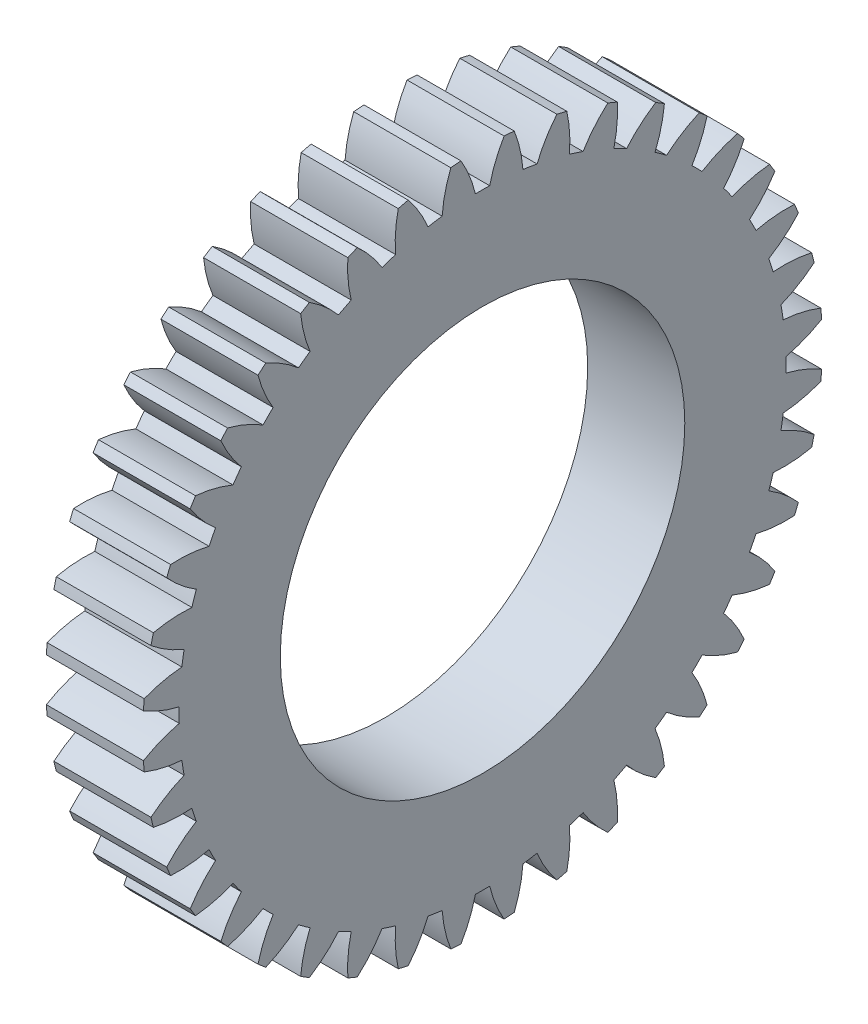
SolidWorks part; units mm, degrees
ref_plane "Plane1" through (0, 0, 0) normal (0, 0, 1) x (1, 0, 0)
ref_plane "Plane2" through (0, 0, 0) normal (0, 1, 0) x (1, 0, 0)
ref_plane "Plane3" through (0, 0, 0) normal (1, 0, 0) x (0, 0, -1)
other "Configuration Table"
sketch "HoldingSke" plane through (0, 0, 0) normal (0, 1, 0) x (1, 0, 0)
  line L0 (0, 0) -> (0.383, -0.3214)
  line L1 (-15, 0) -> (100, 0) construction
  line L2 (0, 0) -> (-2.1039, 2.3779)
  line L3 (0, 0) -> (-11.863, 4.5341)
  line L4 (0, 0) -> (6.6156, 5.5511)
  line L5 (0, 0) -> (-46.8476, -17.4728)
  line L6 (0, 0) -> (-9.9476, -6.7116)
  line L7 (-2.1039, 2.3779) -> (8.6586, 51.2059)
  line L8 (-76.2, 54.61) -> (-71.9, 54.61)
  line L9 (-71.009, 38.7566) -> (-53.1078, 45.2721)
  line L10 (-76.2, 71.12) -> (104.1128, 71.12)
  line L11 (0, 0) -> (-12, 0)
  line L12 (-76.2, 101.6) -> (-76.133, 101.6)
  line L13 (24.9733, 27.94) -> (52.9518, 28.4284)
  line L14 (24.9733, 27.94) -> (24.9743, 27.94)
  line L15 (24.9733, 27.94) -> (100.4006, 29.5858)
  line L16 (-63.627, -2) -> (-12.827, -2)
  circle A0 centre (0, 0) radius 25
  circle A1 centre (0, 0) radius 37.499
  circle A2 centre (0, 0) radius 37.5
  circle A3 centre (0, 0) radius 25
  dimension "MHD" = 74.998
  dimension "Hub_dia" = 75
  dimension "Bore" = 50
  dimension "MBD" = 50
  dimension "Num_teeth" = 40
  dimension "Pitch" = 0.5
  dimension "Overall_len" = 50
  dimension "Show_teeth" = 40
  dimension "Thickness" = 12
  dimension "OAL" = 50.0001
  dimension "T_dim" = 4.3
  dimension "Ap" = 20
  dimension "H" = 19.05
  dimension "Pitch_radius" = 180.3128
  dimension "Width" = 12
  dimension "Backlash" = 0.067
  dimension "Addendum_fac" = 1
  dimension "Dedendum_fac" = 1.25
  dimension "Clearance_fac" = 0.25
  dimension "Dedendum_add" = 0.001
  dimension "Module" = 2
sketch "BasProSke" plane through (0, 0, 0) normal (0, 1, 0) x (1, 0, 0)
  line L0 (-10, 0) -> (60, 0) construction
  line L1 (0, 0) -> (0, 42)
  line L2 (0, 0) -> (12, 0)
  line L3 (12, 0) -> (12, 42)
  line L4 (12, 42) -> (0, 42)
  dimension "Thickness" = 12
  dimension "Diameter" = 84
revolve "Base-Revolve" add sketch "BasProSke" angle 360 about L0
sketch "TooCutSke" plane through (0, 0, 0) normal (1, 0, 0) x (0, 0, -1)
  line L1 (0, 0) -> (0, 107) construction
  line L2 (0, 0) -> (-1.6876, 39.9644) construction
  line L3 (0, 0) -> (-6.2726, 79.7007) construction
  line L4 (-1.6876, 39.9644) -> (-3.1363, 39.8504) construction
  arc A0 (0.8828, 37.4886) -> (-0.8828, 37.4886) centre (0, 0) ccw
  arc A1 (2.6784, 41.94) -> (-2.6784, 41.94) centre (0, 0) ccw
  circle A2 centre (0, 0) radius 40 construction
  circle A3 centre (0, 0) radius 37.5877 construction
  arc A4 (-0.8828, 37.4886) -> (-2.6784, 41.94) centre (-16.451, 33.7965) ccw
  arc A5 (2.6784, 41.94) -> (0.8828, 37.4886) centre (16.451, 33.7965) ccw
  dimension "Root_dia" = 74.998
  dimension "Overcut_dia" = 84.0508
  dimension "Pitch_dia" = 80
  dimension "Base_dia" = 75.1754
  dimension "Flank_rad" = 16
  dimension "Half_ang" = 4.5
  dimension "Half_CT" = 1.4531
extrude "ToothCut" cut sketch "TooCutSke" along normal through all
fillet "Breaks" [suppressed] radius 0.04
fillet "RootFillets" [suppressed] radius 0.501
pattern_circular "TeethCuts" count 40 every 9 about axis through (-10, 0, 0) along (1, 0, 0) of "ToothCut", "RootFillets", "Breaks"
sketch "HubNeaOneSke" plane through (0, 0, 0) normal (-1, 0, 0) x (0, 0, 1)
  circle A0 centre (0, 0) radius 37.499
  dimension "Diameter" = 74.998
extrude "HubNearOne" [suppressed] add sketch "HubNeaOneSke" along normal blind 38.0001
sketch "HubNeaBotSke" plane through (0, 0, 0) normal (-1, 0, 0) x (0, 0, 1)
  circle A0 centre (0, 0) radius 37.499
  dimension "Diameter" = 74.998
extrude "HubNearBoth" [suppressed] add sketch "HubNeaBotSke" along normal blind 19
ref_plane "FarPln" through (12, 0, 0) normal (1, 0, 0) x (0, 0, -1)
sketch "HubFarSke" plane through (12, 0, 0) normal (1, 0, 0) x (0, 0, -1)
  circle A0 centre (0, 0) radius 37.499
  dimension "Diameter" = 74.998
extrude "HubFar" [suppressed] add sketch "HubFarSke" along normal blind 19
sketch "BorSke" plane through (0, 0, 0) normal (1, 0, 0) x (0, 0, -1)
  circle A0 centre (0, 0) radius 25
  dimension "Diameter" = 50
extrude "Bore" cut sketch "BorSke" along normal mid plane 100.0001
sketch "KeySke" plane through (0, 0, 0) normal (1, 0, 0) x (0, 0, -1)
  line L0 (-8, 0) -> (-8, 29.3)
  line L1 (-8, 29.3) -> (8, 29.3)
  line L2 (8, 29.3) -> (8, 0)
  line L3 (0, 0) -> (0, 34) construction
  line L4 (-8, 0) -> (8, 0)
  dimension "Offset" = 29.3
  dimension "Width" = 16
extrude "Keyway" [suppressed] cut sketch "KeySke" along normal mid plane 100.0001
pattern_circular "Keyway2" [suppressed] count 2 every 90 about axis through (-10, 0, 0) along (1, 0, 0)
equation "' \"Module@HoldingSke\" = 6.35"
equation "' \"Num_teeth@HoldingSke\" = 12"
equation "' \"Ap@HoldingSke\" =  20"
equation "' \"Ap@HoldingSke\" = 20"
equation "' \"Width@HoldingSke\" = 0.5 * 25.4"
equation "' \"Hub_dia@HoldingSke\"= 1 * 25.4"
equation "' \"Hub_dia@HoldingSke\" = 1 * 25.4"
equation "' \"Overall_len@HoldingSke\" = 1.0 * 25.4"
equation "' \"Bore@HoldingSke\" = 0.75 * 25.4"
equation "' \"T_dim@HoldingSke\" = 0.1 * 25.4"
equation "' \"Width@KeySke\" = 0.25 * 25.4"
equation "' \"Show_teeth@HoldingSke\" = 13"
equation "' \"Backlash@HoldingSke\" = 0.009 * 25.4"
equation "' \"Addendum_fac@HoldingSke\" = 1.0"
equation "' \"Dedendum_fac@HoldingSke\" = 1.25"
equation "' \"Dedendum_add@HoldingSke\" = 0.00005 * 25.4"
equation "' \"Clearance_fac@HoldingSke\" = 0.25"
equation "\"Pitch@HoldingSke\" = 1 / \"Module@HoldingSke\""
equation "\"Overcut_dia@TooCutSke\" = (\"Num_teeth@HoldingSke\" + 2 * \"Addendum_fac@HoldingSke\") / \"Pitch@HoldingSke\" + 0.002 * 25.4"
equation "\"Pitch_dia@TooCutSke\" = \"Num_teeth@HoldingSke\" / \"Pitch@HoldingSke\""
equation "\"Base_dia@TooCutSke\" = \"Num_teeth@HoldingSke\" / \"Pitch@HoldingSke\" * cos((\"Ap@HoldingSke\"  * 3.14159265 / 180))"
equation "\"Root_dia@TooCutSke\" = (\"Num_teeth@HoldingSke\" + 2) / \"Pitch@HoldingSke\" - 2 * (\"Addendum_fac@HoldingSke\" + \"Dedendum_fac@HoldingSke\") / \"Pitch@HoldingSke\" - \"Dedendum_add@HoldingSke\" * 2"
equation "\"Half_ang@TooCutSke\" = 180 / \"Num_teeth@HoldingSke\""
equation "\"Half_CT@TooCutSke\" = \"Num_teeth@HoldingSke\" / \"Pitch@HoldingSke\" * sin((3.14159265 / 2 / \"Num_teeth@HoldingSke\")) / 2 - 7 * \"Backlash@HoldingSke\" / 4"
equation "\"Flank_rad@TooCutSke\" = \"Num_teeth@HoldingSke\" / \"Pitch@HoldingSke\" / 5"
equation "\"Radius@RootFillets\" = \"Clearance_fac@HoldingSke\" / \"Pitch@HoldingSke\" + \"Dedendum_add@HoldingSke\""
equation "\"Break_rad@Breaks\" = 0.02 / \"Pitch@HoldingSke\""
equation "\"Thickness@HoldingSke\" = \"Width@HoldingSke\""
equation "\"OAL@HoldingSke\" = \"Thickness@HoldingSke\""
equation "\"MHD@HoldingSke\" = (\"Num_teeth@HoldingSke\" + 2) / \"Pitch@HoldingSke\" - 2 * (\"Addendum_fac@HoldingSke\" + \"Dedendum_fac@HoldingSke\")  / \"Pitch@HoldingSke\" - \"Dedendum_add@HoldingSke\" * 2"
equation "\"MBD@HoldingSke\" = (\"Num_teeth@HoldingSke\" + 2) / \"Pitch@HoldingSke\" - 2 * (\"Addendum_fac@HoldingSke\" + \"Dedendum_fac@HoldingSke\")  / \"Pitch@HoldingSke\" - \"Dedendum_add@HoldingSke\" * 2 - 0.002 * 25.4"
equation "\"MHD@HoldingSke\" = ((sgn( \"MHD@HoldingSke\" - \"Hub_dia@HoldingSke\" )-1)*( \"MHD@HoldingSke\" - \"Hub_dia@HoldingSke\" ))/-2+ \"Hub_dia@HoldingSke\""
equation "\"MBD@HoldingSke\" = ((sgn( \"MBD@HoldingSke\" - \"Bore@HoldingSke\" )-1)*( \"MBD@HoldingSke\" - \"Bore@HoldingSke\" ))/-2+ \"Bore@HoldingSke\""
equation "\"OAL@HoldingSke\" = ((sgn( \"OAL@HoldingSke\" - \"Overall_len@HoldingSke\" )+1)*( \"OAL@HoldingSke\" - \"Overall_len@HoldingSke\" ))/2 + \"Overall_len@HoldingSke\" + 0.000002 * 25.4"
equation "\"Num_teeth@TeethCuts\" = int( \"Show_teeth@HoldingSke\" ) + 1"
equation "\"Num_teeth@TeethCuts\" = ((sgn( \"Num_teeth@TeethCuts\" - \"Num_teeth@HoldingSke\" )-1)*( \"Num_teeth@TeethCuts\" - \"Num_teeth@HoldingSke\" ))/-2+ \"Num_teeth@HoldingSke\""
equation "\"Num_teeth@TeethCuts\" = ((sgn( \"Num_teeth@TeethCuts\" - 2.0)+1)*( \"Num_teeth@TeethCuts\" - 2.0))/2 +2.0"
equation "\"Angle@TeethCuts\" = 360.0 / \"Num_teeth@HoldingSke\""
equation "\"Diameter@BasProSke\" = (\"Num_teeth@HoldingSke\" + 2 * \"Addendum_fac@HoldingSke\") / \"Pitch@HoldingSke\""
equation "\"Thickness@BasProSke\"  = \"Thickness@HoldingSke\""
equation "' \"Fillet_rad@BasProSke\" =  \"Thickness@HoldingSke\" * 0.05"
equation "' \"Fillet_rad@BasProSke\" = \"Thickness@HoldingSke\" * 0.05"
equation "\"MHD@HoldingSke\" = ((sgn( \"MHD@HoldingSke\" - \"Root_dia@TooCutSke\" )-1)*( \"MHD@HoldingSke\" - \"Root_dia@TooCutSke\" ))/-2+ \"Root_dia@TooCutSke\""
equation "\"Diameter@HubNeaOneSke\" = \"MHD@HoldingSke\""
equation "\"Length@HubNearOne\" = \"OAL@HoldingSke\" - \"Thickness@BasProSke\""
equation "\"Diameter@HubNeaBotSke\" = \"MHD@HoldingSke\""
equation "\"Length@HubNearBoth\" = ( \"OAL@HoldingSke\" - \"Thickness@BasProSke\" ) / 2.0"
equation "\"Thickness@FarPln\" = \"Thickness@BasProSke\""
equation "\"Diameter@HubFarSke\" = \"MHD@HoldingSke\""
equation "\"Length@HubFar\" = ( \"OAL@HoldingSke\" - \"Thickness@BasProSke\" ) / 2.0"
equation "\"Diameter@BorSke\" = \"MBD@HoldingSke\""
equation "\"D1@Bore\" = \"OAL@HoldingSke\" * 2.0"
equation "\"D1@Keyway\" = \"OAL@HoldingSke\" * 2.0"
equation "\"Offset@KeySke\" = \"T_dim@HoldingSke\" + \"MBD@HoldingSke\" / 2.0"
